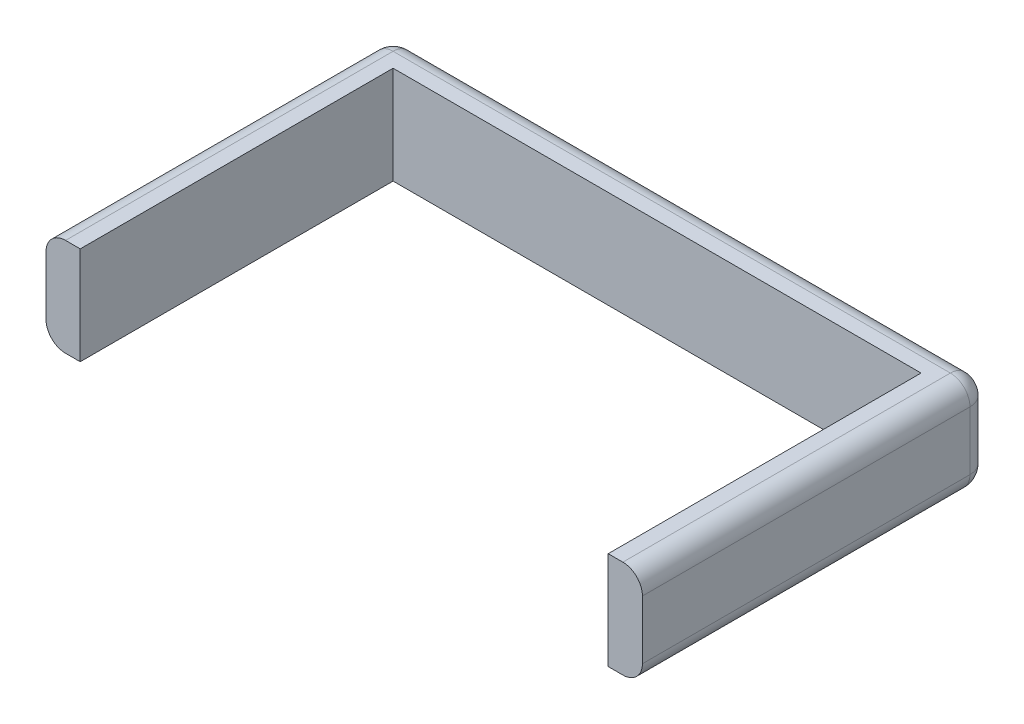
SolidWorks part; units mm, degrees
material "Polyurethane Foam Flexible"
ref_plane "Front Plane" through (0, 0, 0) normal (0, 0, 1) x (1, 0, 0)
ref_plane "Top Plane" through (0, 0, 0) normal (0, 1, 0) x (1, 0, 0)
ref_plane "Right Plane" through (0, 0, 0) normal (1, 0, 0) x (0, 0, -1)
sketch "Sketch2" plane through (0, 0, 0) normal (0, 1, 0) x (1, 0, 0)
  line L0 (0, 450.85) -> (0, 406.4) construction
  line L1 (-387.35, 450.85) -> (387.35, 450.85)
  line L2 (387.35, 450.85) -> (387.35, 0)
  line L3 (387.35, 0) -> (342.9, 0)
  line L4 (342.9, 0) -> (342.9, 406.4)
  line L5 (342.9, 406.4) -> (-342.9, 406.4)
  line L6 (-342.9, 0) -> (-342.9, 406.4)
  line L7 (-387.35, 0) -> (-342.9, 0)
  line L8 (-387.35, 450.85) -> (-387.35, 0)
  point P9 (0, 406.4)
  dimension "D1" = 774.7
  dimension "D2" = 450.85
  dimension "D3" = 44.45
extrude "Boss-Extrude1" add sketch "Sketch2" along normal blind 127
fillet "Fillet1" radius 25.4 8 edges at (387.35, 63.5, -450.85) (0, 127, -450.85) (-387.35, 63.5, -450.85) (0, 0, -450.85) (387.35, 0, -225.425) (387.35, 127, -225.425) (-387.35, 0, -225.425) (-387.35, 127, -225.425)
